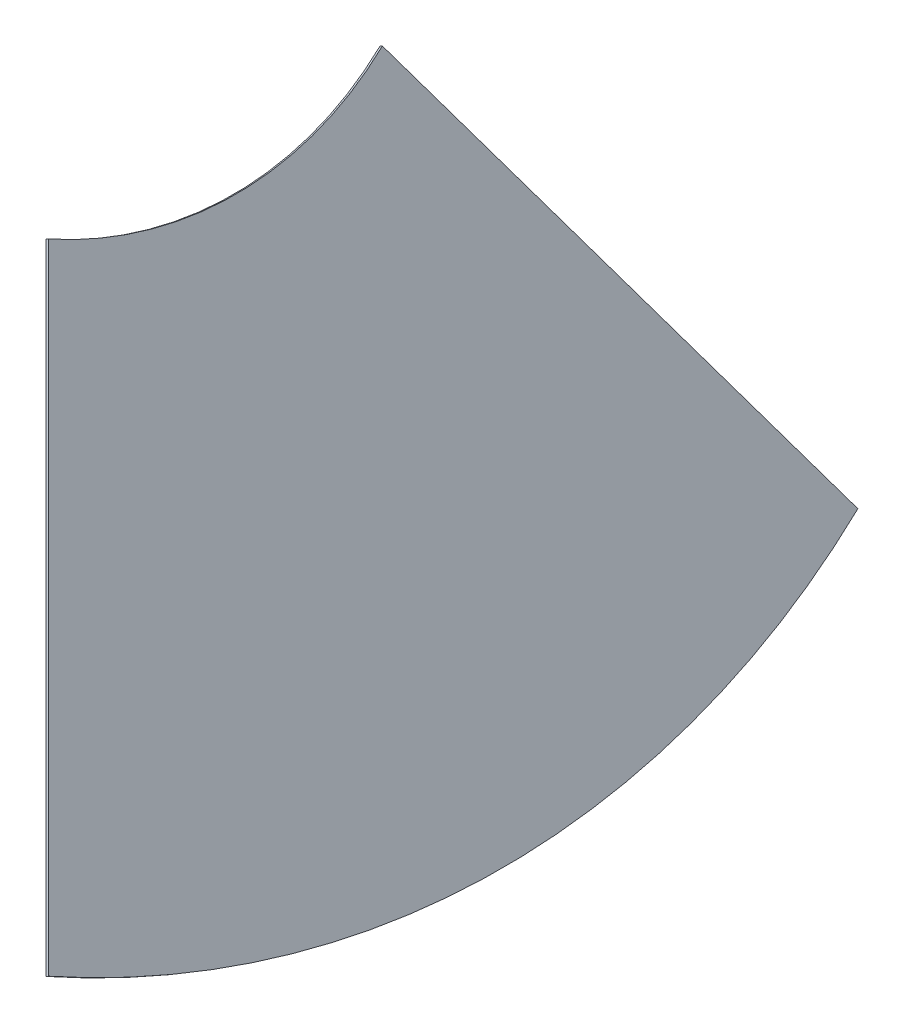
SolidWorks part; units mm, degrees
ref_plane "Front Plane" through (0, 0, 0) normal (0, 0, 1) x (1, 0, 0)
ref_plane "Top Plane" through (0, 0, 0) normal (0, 1, 0) x (1, 0, 0)
ref_plane "Right Plane" through (0, 0, 0) normal (1, 0, 0) x (0, 0, -1)
sketch "Sketch2" plane through (85.4357, -57.3957, -3.7508) normal (-0.86, -0.5103, 0) x (0.485, -0.8174, 0.311)
  line L19 (-40.9158, -59.9662) -> (121.2931, -223.0403)
  line L20 (232.0345, 115.1737) -> (4.803, 79.5267)
  line L25 (119.0421, -225.2794) -> (-92.525, -12.5838)
  line L26 (-64.3408, 68.6797) -> (-64.8328, 71.8164)
  line L30 (-90.274, -10.3448) -> (121.2931, -223.0403)
  line L31 (-90.274, -10.3448) -> (121.2931, -223.0403) construction
  line L34 (232.0345, 115.1737) -> (-64.3408, 68.6797)
  line L35 (232.0345, 115.1737) -> (-64.3408, 68.6797) construction
  line L36 (121.2931, -223.0403) -> (119.0421, -225.2794)
  line L38 (-64.8328, 71.8164) -> (231.5424, 118.3104)
  line L39 (-64.3408, 68.6797) -> (232.0345, 115.1737) construction
  line L40 (121.2931, -223.0403) -> (119.0421, -225.2794) construction
  line L41 (-92.525, -12.5838) -> (-90.274, -10.3448)
  line L42 (-92.525, -12.5838) -> (-90.274, -10.3448)
  line L43 (231.5424, 118.3104) -> (232.0345, 115.1737)
  line L44 (231.5424, 118.3104) -> (232.0345, 115.1737) construction
  line L45 (-64.3408, 68.6797) -> (-64.8328, 71.8164)
  line L46 (-64.3408, 68.6797) -> (-64.8328, 71.8164)
  line L47 (-40.9158, -59.9662) -> (-53.2133, -72.1984) construction
  line L48 (121.2931, -223.0403) -> (-90.274, -10.3448) construction
  arc A5 (232.0345, 115.1737) -> (121.2931, -223.0403) centre (-154.5749, 54.5242) cw
  arc A6 (4.803, 79.5267) -> (-40.9158, -59.9662) centre (-154.575, 54.5242) cw
  point P6 (-34.7089, -66.2062)
  dimension "D1" = 50
extrude "Boss-Extrude1" add sketch "Sketch2" along normal mid plane 1.27 contours L19 A6 L20 A5
